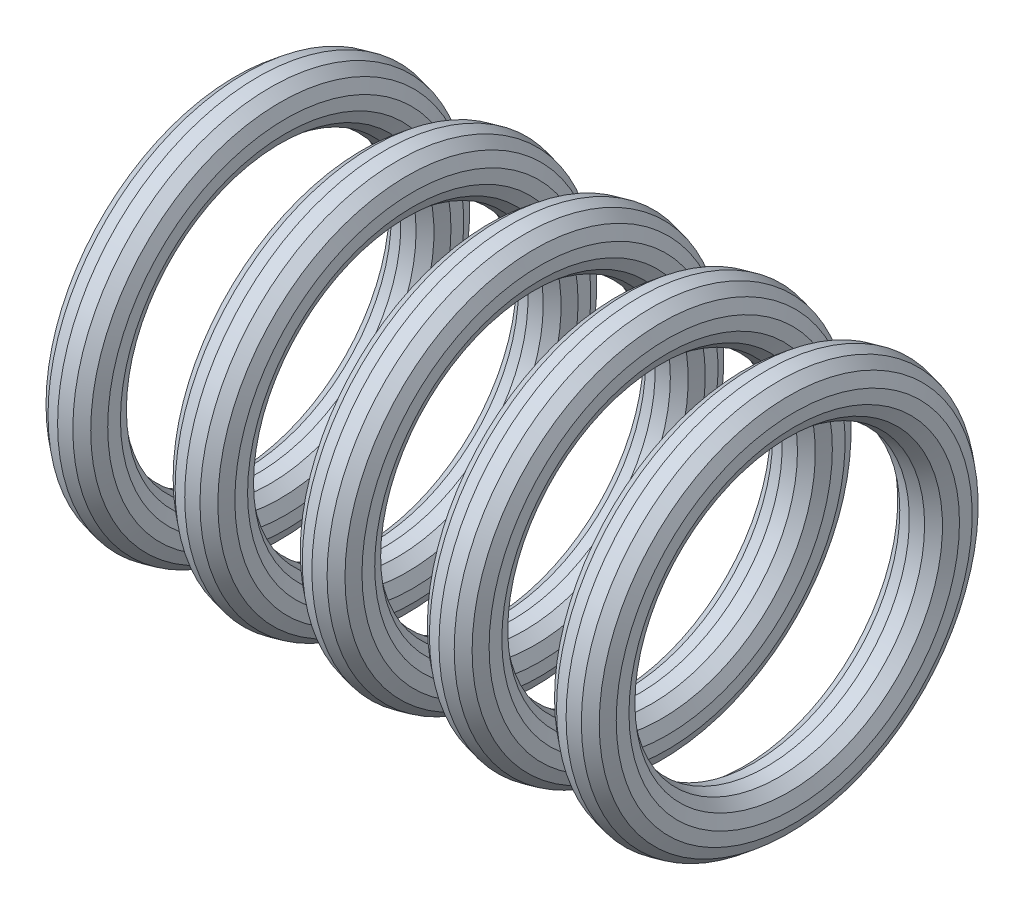
SolidWorks part; units mm, degrees
ref_plane "前视基准面" through (0, 0, 0) normal (0, 0, 1) x (1, 0, 0)
ref_plane "上视基准面" through (0, 0, 0) normal (0, 1, 0) x (1, 0, 0)
ref_plane "右视基准面" through (0, 0, 0) normal (1, 0, 0) x (0, 0, -1)
other "Configuration Table"
sketch "草图1" plane through (0, 0, 0) normal (0, 0, 1) x (1, 0, 0)
  line L0 (-2, 0) -> (22, 0) construction
  line L1 (1, 7) -> (1.4339, 6.901)
  line L2 (1.4339, 6.901) -> (1.7818, 6.6235)
  line L3 (1.7818, 6.6235) -> (1.9749, 6.2225)
  line L4 (1.9749, 6.2225) -> (1.9749, 5.7775)
  line L5 (1.9749, 5.7775) -> (1.7818, 5.3765)
  line L6 (1.7818, 5.3765) -> (1.4339, 5.099)
  line L7 (1.4339, 5.099) -> (1, 5)
  line L8 (1, 5) -> (0.5661, 5.099)
  line L9 (0.5661, 5.099) -> (0.2182, 5.3765)
  line L10 (0.2182, 5.3765) -> (0.0251, 5.7775)
  line L11 (0.0251, 5.7775) -> (0.0251, 6.2225)
  line L12 (0.0251, 6.2225) -> (0.2182, 6.6235)
  line L13 (0.2182, 6.6235) -> (0.5661, 6.901)
  line L14 (0.5661, 6.901) -> (1, 7)
revolve "旋转1" add sketch "草图1" angle 360 about L0
sketch "草图2" plane through (0, 0, 0) normal (0, 0, 1) x (1, 0, 0)
  line L0 (-2, 0) -> (22, 0) construction
  line L1 (5.4444, 7) -> (5.8783, 6.901)
  line L2 (5.8783, 6.901) -> (6.2263, 6.6235)
  line L3 (6.2263, 6.6235) -> (6.4194, 6.2225)
  line L4 (6.4194, 6.2225) -> (6.4194, 5.7775)
  line L5 (6.4194, 5.7775) -> (6.2263, 5.3765)
  line L6 (6.2263, 5.3765) -> (5.8783, 5.099)
  line L7 (5.8783, 5.099) -> (5.4444, 5)
  line L8 (5.4444, 5) -> (5.0106, 5.099)
  line L9 (5.0106, 5.099) -> (4.6626, 5.3765)
  line L10 (4.6626, 5.3765) -> (4.4695, 5.7775)
  line L11 (4.4695, 5.7775) -> (4.4695, 6.2225)
  line L12 (4.4695, 6.2225) -> (4.6626, 6.6235)
  line L13 (4.6626, 6.6235) -> (5.0106, 6.901)
  line L14 (5.0106, 6.901) -> (5.4444, 7)
revolve "旋转2" add sketch "草图2" angle 360 about L0
sketch "草图3" plane through (0, 0, 0) normal (0, 0, 1) x (1, 0, 0)
  line L0 (-2, 0) -> (22, 0) construction
  line L1 (9.8889, 7) -> (10.3228, 6.901)
  line L2 (10.3228, 6.901) -> (10.6707, 6.6235)
  line L3 (10.6707, 6.6235) -> (10.8638, 6.2225)
  line L4 (10.8638, 6.2225) -> (10.8638, 5.7775)
  line L5 (10.8638, 5.7775) -> (10.6707, 5.3765)
  line L6 (10.6707, 5.3765) -> (10.3228, 5.099)
  line L7 (10.3228, 5.099) -> (9.8889, 5)
  line L8 (9.8889, 5) -> (9.455, 5.099)
  line L9 (9.455, 5.099) -> (9.1071, 5.3765)
  line L10 (9.1071, 5.3765) -> (8.914, 5.7775)
  line L11 (8.914, 5.7775) -> (8.914, 6.2225)
  line L12 (8.914, 6.2225) -> (9.1071, 6.6235)
  line L13 (9.1071, 6.6235) -> (9.455, 6.901)
  line L14 (9.455, 6.901) -> (9.8889, 7)
revolve "旋转3" add sketch "草图3" angle 360 about L0
sketch "草图4" plane through (0, 0, 0) normal (0, 0, 1) x (1, 0, 0)
  line L0 (-2, 0) -> (22, 0) construction
  line L1 (14.3333, 7) -> (14.7672, 6.901)
  line L2 (14.7672, 6.901) -> (15.1152, 6.6235)
  line L3 (15.1152, 6.6235) -> (15.3083, 6.2225)
  line L4 (15.3083, 6.2225) -> (15.3083, 5.7775)
  line L5 (15.3083, 5.7775) -> (15.1152, 5.3765)
  line L6 (15.1152, 5.3765) -> (14.7672, 5.099)
  line L7 (14.7672, 5.099) -> (14.3333, 5)
  line L8 (14.3333, 5) -> (13.8994, 5.099)
  line L9 (13.8994, 5.099) -> (13.5515, 5.3765)
  line L10 (13.5515, 5.3765) -> (13.3584, 5.7775)
  line L11 (13.3584, 5.7775) -> (13.3584, 6.2225)
  line L12 (13.3584, 6.2225) -> (13.5515, 6.6235)
  line L13 (13.5515, 6.6235) -> (13.8994, 6.901)
  line L14 (13.8994, 6.901) -> (14.3333, 7)
revolve "旋转4" add sketch "草图4" angle 360 about L0
sketch "草图5" plane through (0, 0, 0) normal (0, 0, 1) x (1, 0, 0)
  line L0 (-2, 0) -> (22, 0) construction
  line L1 (18.7778, 7) -> (19.2117, 6.901)
  line L2 (19.2117, 6.901) -> (19.5596, 6.6235)
  line L3 (19.5596, 6.6235) -> (19.7527, 6.2225)
  line L4 (19.7527, 6.2225) -> (19.7527, 5.7775)
  line L5 (19.7527, 5.7775) -> (19.5596, 5.3765)
  line L6 (19.5596, 5.3765) -> (19.2117, 5.099)
  line L7 (19.2117, 5.099) -> (18.7778, 5)
  line L8 (18.7778, 5) -> (18.3439, 5.099)
  line L9 (18.3439, 5.099) -> (17.9959, 5.3765)
  line L10 (17.9959, 5.3765) -> (17.8028, 5.7775)
  line L11 (17.8028, 5.7775) -> (17.8028, 6.2225)
  line L12 (17.8028, 6.2225) -> (17.9959, 6.6235)
  line L13 (17.9959, 6.6235) -> (18.3439, 6.901)
  line L14 (18.3439, 6.901) -> (18.7778, 7)
revolve "旋转5" add sketch "草图5" angle 360 about L0
